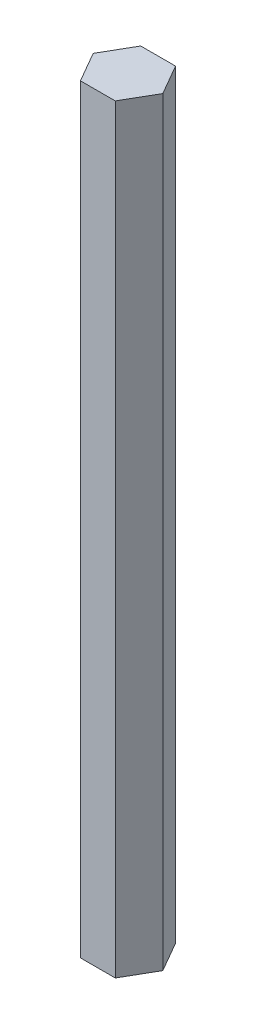
SolidWorks part; units mm, degrees
ref_plane "Alzado" through (0, 0, 0) normal (0, 0, 1) x (1, 0, 0)
ref_plane "Planta" through (0, 0, 0) normal (0, 1, 0) x (1, 0, 0)
ref_plane "Vista lateral" through (0, 0, 0) normal (1, 0, 0) x (0, 0, -1)
sketch "Croquis1" plane through (0, 0, 0) normal (0, 1, 0) x (1, 0, 0)
  line L1 (7.3323, 0) -> (3.6662, 6.35)
  line L2 (3.6662, 6.35) -> (-3.6662, 6.35)
  line L3 (-3.6662, 6.35) -> (-7.3323, 0)
  line L4 (-7.3323, 0) -> (-3.6662, -6.35)
  line L5 (-3.6662, -6.35) -> (3.6662, -6.35)
  line L6 (3.6662, -6.35) -> (7.3323, 0)
  circle A0 centre (0, 0) radius 6.35 construction
  dimension "D1" = 12.7
extrude "Saliente-Extruir1" add sketch "Croquis1" along normal blind 160
